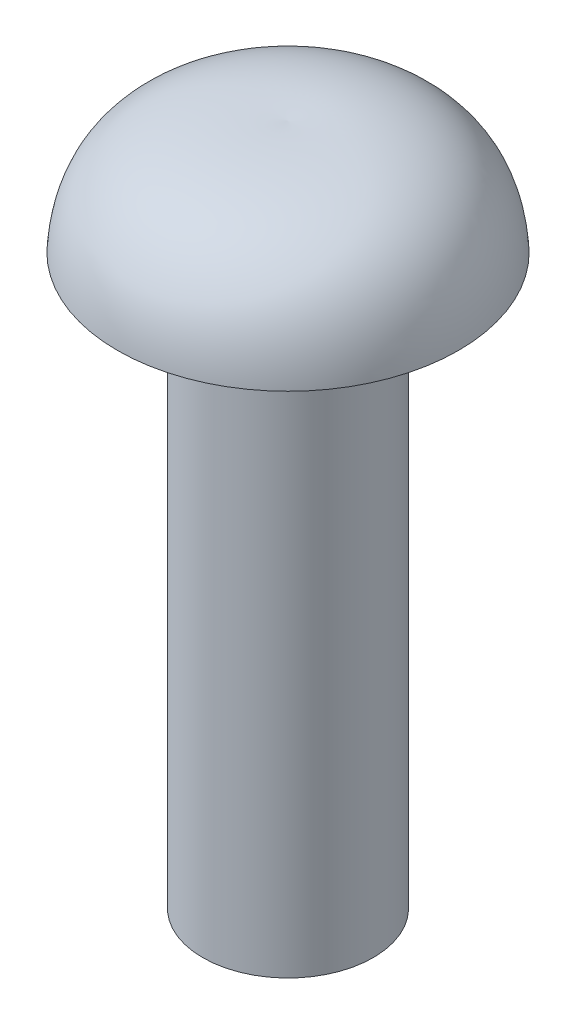
SolidWorks part; units mm, degrees
material "炭素鋼(普通)"
ref_plane "正面" through (0, 0, 0) normal (0, 0, 1) x (1, 0, 0)
ref_plane "平面" through (0, 0, 0) normal (0, 1, 0) x (1, 0, 0)
ref_plane "右側面" through (0, 0, 0) normal (1, 0, 0) x (0, 0, -1)
sketch "ｽｹｯﾁ2" plane through (0, 0, 0) normal (0, 1, 0) x (1, 0, 0)
  circle A0 centre (0, 0) radius 1.5
  dimension "D1" = 3
extrude "ﾎﾞｽ - 押し出し1" add sketch "ｽｹｯﾁ2" along normal blind 10
sketch "ｽｹｯﾁ4" plane through (0, 0, 0) normal (0, 0, 1) x (1, 0, 0)
  line L0 (0, 10) -> (0, 0) construction
  line L1 (1.5, 10) -> (-1.5, 10) construction
  line L2 (0, 10) -> (3, 10)
  line L3 (0, 12) -> (0, 10)
  spline S0 degree 2 poles (0, 12) (2.8509, 12.1998) (3, 10) knots 0 0 0 1 1 1
  dimension "D1" = 2
  dimension "D2" = 3
revolve "回転1" add sketch "ｽｹｯﾁ4" angle 360 about L0
